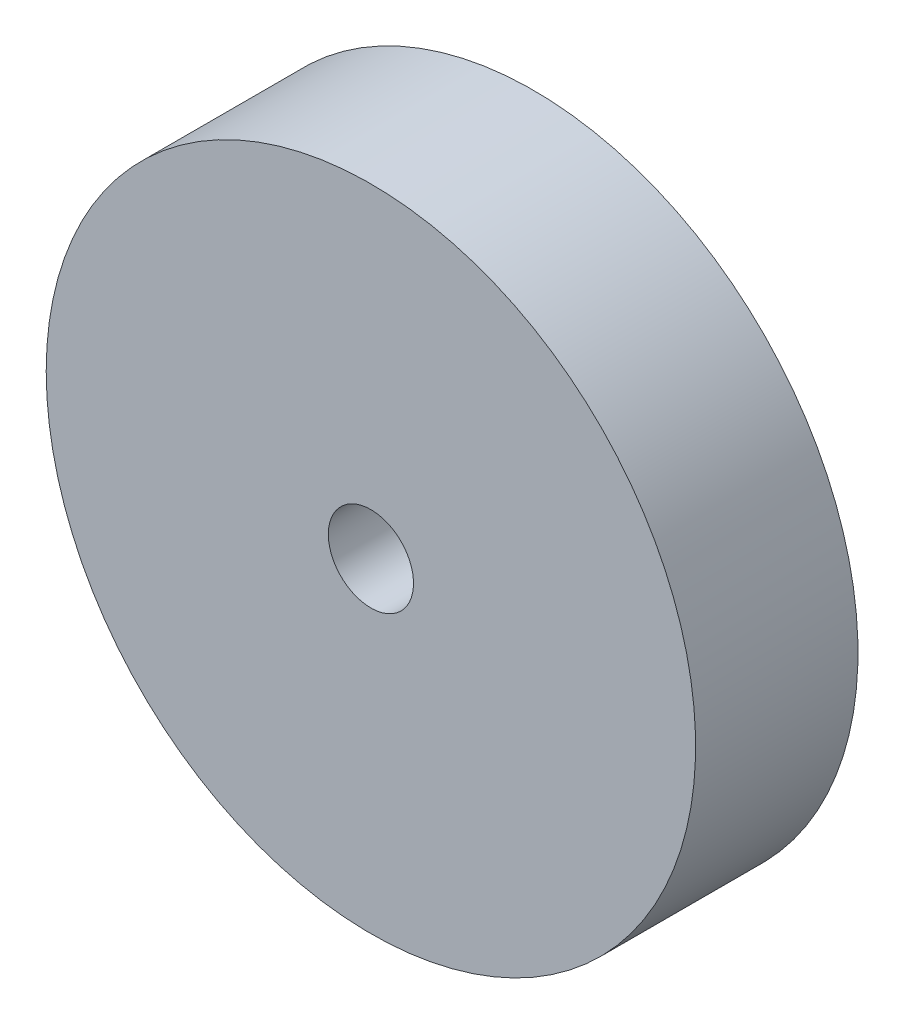
SolidWorks part; units mm, degrees
ref_plane "Front Plane" through (0, 0, 0) normal (0, 0, 1) x (1, 0, 0)
ref_plane "Top Plane" through (0, 0, 0) normal (0, 1, 0) x (1, 0, 0)
ref_plane "Right Plane" through (0, 0, 0) normal (1, 0, 0) x (0, 0, -1)
sketch "Sketch2" plane through (0, 0, 0) normal (0, 0, 1) x (1, 0, 0)
  circle A0 centre (0, 0) radius 38.1
  dimension "D1" = 76.2
extrude "Boss-Extrude1" add sketch "Sketch2" along normal blind 19.05
sketch "Sketch3" plane through (0, 0, 0) normal (0, 0, -1) x (-1, 0, 0)
  circle A0 centre (0, 0) radius 5
  dimension "D1" = 10
extrude "Cut-Extrude1" cut sketch "Sketch3" against normal through all
